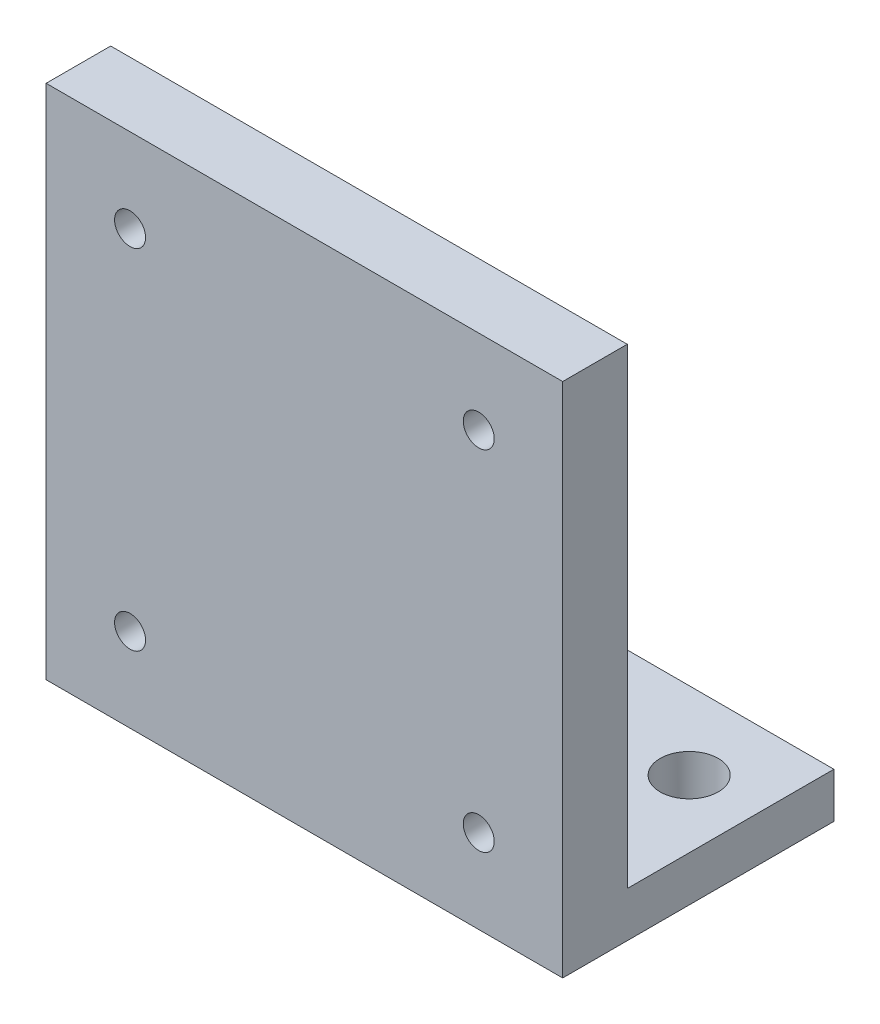
SolidWorks part; units mm, degrees
ref_plane "前视基准面" through (0, 0, 0) normal (0, 0, 1) x (1, 0, 0)
ref_plane "上视基准面" through (0, 0, 0) normal (0, 1, 0) x (1, 0, 0)
ref_plane "右视基准面" through (0, 0, 0) normal (1, 0, 0) x (0, 0, -1)
sketch "草图1" plane through (0, 0, 0) normal (0, 1, 0) x (1, 0, 0)
  line L1 (-20, 20) -> (20, 20)
  line L2 (-20, 20) -> (-20, -20)
  line L3 (-20, -20) -> (20, -20)
  line L4 (20, 20) -> (20, -20)
  line L5 (-20, 20) -> (20, -20) construction
  line L6 (-20, -20) -> (20, 20) construction
  point P0 (0, 0)
  dimension "D1" = 40
  dimension "D2" = 40
extrude "凸台-拉伸1" add sketch "草图1" along normal blind 5
sketch "草图2" plane through (0, 5, 0) normal (0, 1, 0) x (1, 0, 0)
  line L0 (-20, 20) -> (-20, -20) construction
  line L1 (-20, 4) -> (20, 4)
  line L2 (-20, 4) -> (-20, -1)
  line L3 (-20, -1) -> (20, -1)
  line L4 (20, 4) -> (20, -1)
  line L5 (20, 20) -> (-20, 20) construction
  dimension "D1" = 5
  dimension "D2" = 16
extrude "凸台-拉伸2" add sketch "草图2" along normal blind 35
sketch "草图3" plane through (0, 0, 0) normal (0, -1, 0) x (1, 0, 0)
  line L0 (20, 20) -> (20, -20) construction
  line L1 (-20, 20) -> (20, 20)
  line L2 (-20, 20) -> (-20, 10)
  line L3 (-20, 10) -> (20, 10)
  line L4 (20, 20) -> (20, 10)
  dimension "D1" = 10
extrude "凸台-拉伸3" add sketch "草图3" along normal blind 5
sketch "草图4" plane through (0, -5, 0) normal (0, -1, 0) x (1, 0, 0)
  line L4 (20, 10) -> (-20, 10)
  line L5 (-20, 10) -> (-20, -20)
  line L6 (-20, -20) -> (20, -20)
  line L7 (20, -20) -> (20, 10)
  line L9 (-20, 10) -> (-20, -20)
  line L10 (-20, -20) -> (20, -20)
  line L11 (20, -20) -> (20, 10)
  line L12 (-20, 20) -> (-20, 10)
  line L13 (-20, 10) -> (20, 10)
  line L14 (20, 10) -> (20, 20)
  line L15 (20, 20) -> (-20, 20)
  line L16 (-20, 20) -> (-20, 10)
  line L18 (20, 10) -> (20, 20)
  line L19 (20, 20) -> (-20, 20)
  dimension "D1" = 0
  dimension "D2" = 0
extrude "凸台-拉伸4" add sketch "草图4" along normal blind 5
sketch "草图5" plane through (0, 5, 0) normal (0, 1, 0) x (1, 0, 0)
  line L0 (0, 0) -> (0, 3.825) construction
  line L1 (20, 20) -> (-20, 20) construction
  circle A0 centre (-14.7951, 14) radius 2.25
  circle A1 centre (14.7951, 14) radius 2.25
  dimension "D1" = 4.5
  dimension "D2" = 6
extrude "切除-拉伸1" cut sketch "草图5" against normal blind 20
sketch "草图6" plane through (-20, 0, 0) normal (-1, 0, 0) x (0, 0, 1)
  line L0 (10, 0) -> (20, 0)
  line L12 (-20, 0) -> (10, 0)
  line L13 (10, 0) -> (10, -5)
  line L14 (10, -5) -> (-20, -5)
  line L15 (-20, -5) -> (-20, -10)
  line L16 (-20, -10) -> (20, -10)
  line L17 (20, -10) -> (20, 5)
  line L18 (20, 5) -> (1, 5)
  line L19 (1, 5) -> (1, 40)
  line L20 (1, 40) -> (-4, 40)
  line L21 (-4, 40) -> (-4, 5)
  line L22 (-4, 5) -> (-20, 5)
  line L23 (-20, 5) -> (-20, 0)
  line L25 (10, 0) -> (10, -5)
  line L26 (10, -5) -> (-20, -5)
  line L27 (-20, -5) -> (-20, -10)
  line L28 (-20, -10) -> (20, -10)
  line L29 (20, -10) -> (20, 0)
  dimension "D1" = 0
extrude "切除-拉伸2" cut sketch "草图6" against normal up to surface (40 mm away) up to face at (20, 5.8333, -2.1667)
sketch "草图7" plane through (0, 5, 0) normal (0, 1, 0) x (1, 0, 0)
  line L4 (20, -1) -> (-20, -1)
  line L5 (-20, -1) -> (-20, -20)
  line L6 (-20, -20) -> (20, -20)
  line L7 (20, -20) -> (20, -1)
  line L8 (20, -1) -> (-20, -1)
  line L9 (-20, -1) -> (-20, -20)
  line L10 (-20, -20) -> (20, -20)
  line L11 (20, -20) -> (20, -1)
  dimension "D1" = 0
extrude "切除-拉伸3" cut sketch "草图7" against normal blind 20
sketch "草图8" plane through (0, 0, -20) normal (0, 0, -1) x (-1, 0, 0)
  line L0 (-20, 5) -> (-20, 0) construction
  line L1 (-20, 5) -> (20, 5)
  line L2 (-20, 5) -> (-20, 3.5)
  line L3 (-20, 3.5) -> (20, 3.5)
  line L4 (20, 5) -> (20, 3.5)
  dimension "D1" = 1.5
extrude "切除-拉伸4" cut sketch "草图8" against normal up to surface (16 mm away) up to face at (0, 22.5, -4)
sketch "草图9" plane through (0, 0, 1) normal (0, 0, 1) x (1, 0, 0)
  line L0 (20, 0) -> (-20, 0) construction
  circle A1 centre (13.5, 6.5) radius 1.2
  circle A3 centre (-13.5, 6.5) radius 1.2
  circle A5 centre (-13.5, 33.5) radius 1.2
  circle A7 centre (13.5, 33.5) radius 1.2
  dimension "D1" = 27
  dimension "D2" = 6.5
extrude "切除-拉伸5" cut sketch "草图9" against normal blind 20
